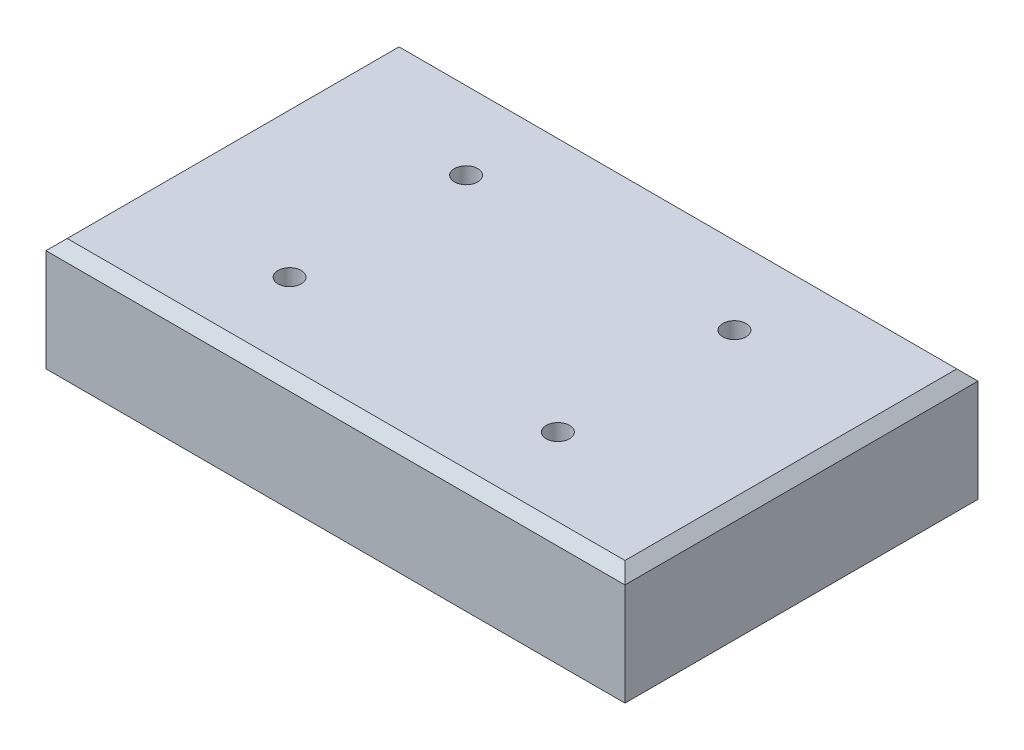
SolidWorks part; units mm, degrees
ref_plane "Front Plane" through (0, 0, 0) normal (0, 0, 1) x (1, 0, 0)
ref_plane "Top Plane" through (0, 0, 0) normal (0, 1, 0) x (1, 0, 0)
ref_plane "Right Plane" through (0, 0, 0) normal (1, 0, 0) x (0, 0, -1)
sketch "Sketch1" plane through (0, 0, 0) normal (0, 1, 0) x (1, 0, 0)
  line L1 (-41, 25) -> (41, 25)
  line L2 (-41, 25) -> (-41, -25)
  line L3 (-41, -25) -> (41, -25)
  line L4 (41, 25) -> (41, -25)
  line L5 (-41, 25) -> (41, -25) construction
  line L6 (-41, -25) -> (41, 25) construction
  point P0 (0, 0)
  dimension "D1" = 82
  dimension "D2" = 50
extrude "Boss-Extrude1" add sketch "Sketch1" along normal blind 16
sketch "Sketch2" plane through (0, 16, 0) normal (0, 1, 0) x (1, 0, 0)
  line L1 (-19, 12.5) -> (19, 12.5) construction
  line L2 (-19, 12.5) -> (-19, -12.5) construction
  line L3 (-19, -12.5) -> (19, -12.5) construction
  line L4 (19, 12.5) -> (19, -12.5) construction
  line L5 (-19, 12.5) -> (19, -12.5) construction
  line L6 (-19, -12.5) -> (19, 12.5) construction
  point P0 (0, 0)
  point P1 (19, -12.5)
  point P2 (-19, 12.5)
  point P3 (-19, -12.5)
  point P4 (19, 12.5)
  point P14 (-19, 12.5)
  point P16 (19, 12.5)
  point P18 (19, -12.5)
  dimension "D1" = 38
  dimension "D2" = 25
sketch "Sketch10" plane through (0, 16, 0) normal (0, 1, 0) x (1, 0, 0)
  point P0 (-19, 12.5)
  point P3 (19, 12.5)
  point P6 (19, -12.5)
  point P9 (-19, -12.5)
hole_wizard "M4 Tapped Hole1" positions "Sketch10" profile "Sketch9" tap size "M4" standard "DIN"
sketch "Sketch9" plane through (-19, 16, -12.5) normal (1, 0, 0) x (0, 0, 1)
  line L0 (0, 0) -> (0, 8)
  line L1 (0, 8) -> (1.65, 7.0086)
  line L2 (1.65, 7.0086) -> (1.65, 0)
  line L5 (1.65, 0) -> (0, 0)
  line L10 (0, 8) -> (-1.65, 7.0086) construction
  line L11 (0, -6.35) -> (0, 107.95) construction
  dimension "Tap Drill Dia." = 3.3
  dimension "Tap Drill Depth" = 8
  dimension "Drill Angle" = 118
cosmetic thread "Hole Thread1" parameters "D1"=6, "D2"=4
cosmetic thread "Hole Thread2" parameters "D1"=6, "D2"=4
cosmetic thread "Hole Thread3" parameters "D1"=6, "D2"=4
cosmetic thread "Hole Thread4" parameters "D1"=6, "D2"=4
chamfer "Chamfer1" distance 1.5 angle 45 4 edges at (-41, 16, 0) (0, 16, -25) (41, 16, 0) (0, 16, 25)
